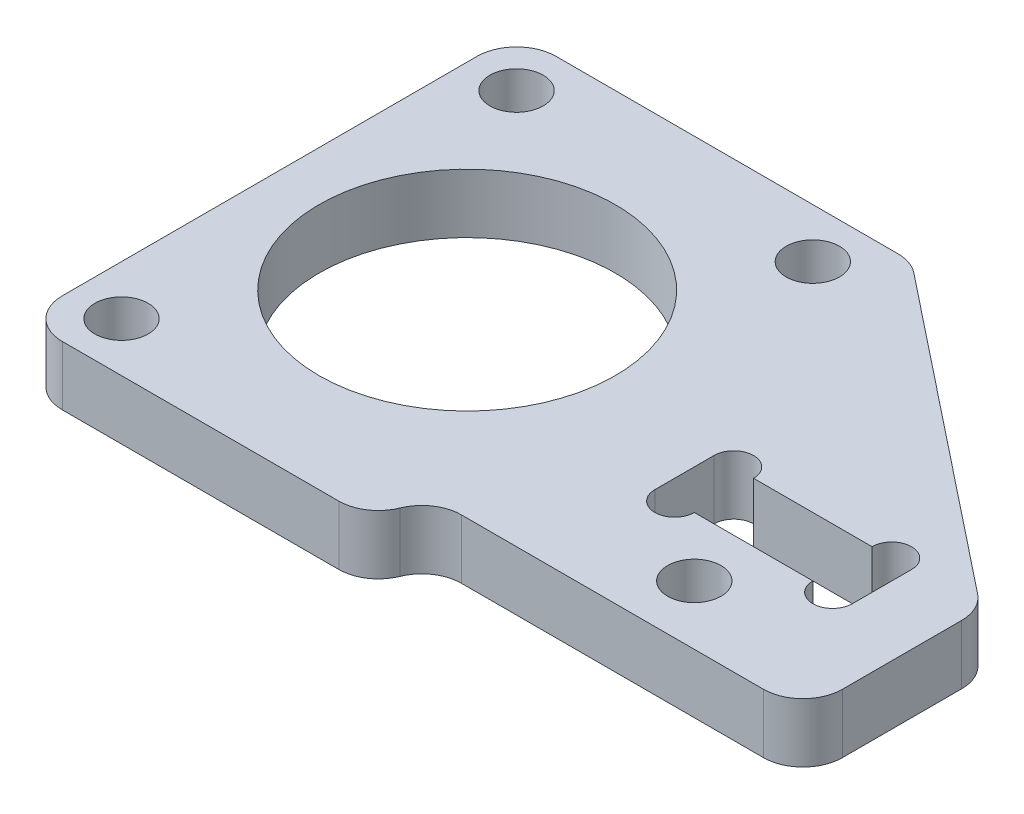
SolidWorks part; units mm, degrees
material "Thornel Mat VMA"
ref_plane "前视基准面" through (0, 0, 0) normal (0, 0, 1) x (1, 0, 0)
ref_plane "上视基准面" through (0, 0, 0) normal (0, 1, 0) x (1, 0, 0)
ref_plane "右视基准面" through (0, 0, 0) normal (1, 0, 0) x (0, 0, -1)
sketch "草图1" plane through (0, 0, 0) normal (0, 1, 0) x (1, 0, 0)
  line L1 (-10, -12.5) -> (0, -12.5)
  line L2 (-10, -12.5) -> (-10, 12.5)
  line L3 (-10, 12.5) -> (10, 12.5)
  line L5 (0, 12.5) -> (0, -12.5) construction
  line L6 (-10, 0) -> (10, 0) construction
  line L11 (10, -4) -> (10, 12.5)
  line L12 (10, -4) -> (27, -4)
  line L14 (8, -10) -> (27, -10)
  line L15 (27, -4) -> (27, -10)
  line L16 (8, -10) -> (8, -12.5)
  line L17 (8, -12.5) -> (0, -12.5)
  circle A0 centre (0, 0) radius 7.5
  point P0 (0, 0)
  dimension "D2" = 15
  dimension "D1" = 20
  dimension "D3" = 17
  dimension "D4" = 6
  dimension "D5" = 25
  dimension "D6" = 10
  dimension "D7" = 2
extrude "凸台-拉伸1" add sketch "草图1" along normal blind 3
sketch "草图3" plane through (0, 3, 0) normal (0, 1, 0) x (1, 0, 0)
  line L0 (27, -7) -> (10, -7) construction
  line L4 (18.5, -7) -> (18.5, -4) construction
  line L6 (10, -4) -> (10, 12.5) construction
  line L7 (27, -10) -> (27, -4) construction
  line L8 (27, -4) -> (10, -4) construction
  line L9 (10, 0) -> (0, 0) construction
  line L10 (0, 0) -> (0, -12.5) construction
  line L11 (-10, -12.5) -> (8, -12.5) construction
  circle A0 centre (18.5, -7) radius 1.35
  circle A2 centre (-7.5, 10) radius 1.35
  circle A3 centre (-7.5, -10) radius 1.35
  circle A4 centre (7.5, -10) radius 1.35 construction
  circle A5 centre (7.5, 10) radius 1.35
  dimension "D2" = 2.7
  dimension "D3" = 15
  dimension "D4" = 20
extrude "切除-拉伸1" cut sketch "草图3" against normal through all
sketch "草图5" plane through (0, 3, 0) normal (0, 1, 0) x (1, 0, 0)
  line L0 (27, -4) -> (27, -1)
  line L6 (27, -1) -> (10, 12.5)
  line L7 (10, 12.5) -> (10, -4)
  line L8 (18.5, -7) -> (18.5, -2.5) construction
  line L9 (10, -4) -> (27, -4)
  line L10 (13.5, -1) -> (23.5, -1)
  line L11 (13.5, -1) -> (13.5, -4)
  line L12 (13.5, -4) -> (23.5, -4)
  line L13 (23.5, -1) -> (23.5, -4)
  line L14 (13.5, -1) -> (23.5, -4) construction
  line L15 (13.5, -4) -> (23.5, -1) construction
  circle A0 centre (18.5, -7) radius 1.35 construction
  circle A1 centre (18.5, -7) radius 1.35 construction
  point P8 (18.5, -2.5)
  line M9 (10, -4) -> (10, 12.5)
  line M16 (27, -4) -> (10, -4)
  dimension "D1" = 3
  dimension "D2" = 3
  dimension "D3" = 10
extrude "凸台-拉伸2" add sketch "草图5" against normal up to surface (3 mm away) contours L10 L13 L0 L6 L9 L11 M16 M9 up to face at (18.5, 0, 8.35)
sketch "草图7" plane through (0, 3, 0) normal (0, 1, 0) x (1, 0, 0)
  line L1 (13.5, -1) -> (23.5, -1) construction
  line L3 (23.5, -1) -> (21.5, -1)
  line L8 (13.5, -2.5) -> (18.5, -2.5) construction
  line L9 (13.5, -1) -> (13.5, -4) construction
  line L10 (18.5, -2.5) -> (18.5, -4) construction
  line L11 (23.5, -4) -> (13.5, -4) construction
  line L12 (13.5, -1) -> (15.5, -1)
  line L13 (13.5, -4) -> (15.5, -4)
  line L14 (23.5, -4) -> (21.5, -4)
  arc A4 (23.5, -1) -> (21.5, -1) centre (22.5, -1) ccw
  arc A5 (13.5, -1) -> (15.5, -1) centre (14.5, -1) cw
  arc A6 (13.5, -4) -> (15.5, -4) centre (14.5, -4) ccw
  arc A7 (23.5, -4) -> (21.5, -4) centre (22.5, -4) cw
  dimension "D1" = 2
extrude "切除-拉伸3" cut sketch "草图7" against normal through all
fillet "圆角1" radius 2 4 edges at (-10, 1.5, 12.5) (-10, 1.5, -12.5) (27, 1.5, 10) (8, 1.5, 12.5)
fillet "圆角2" radius 2 3 edges at (8, 1.5, 10) (10, 1.5, -12.5) (27, 1.5, 1)
